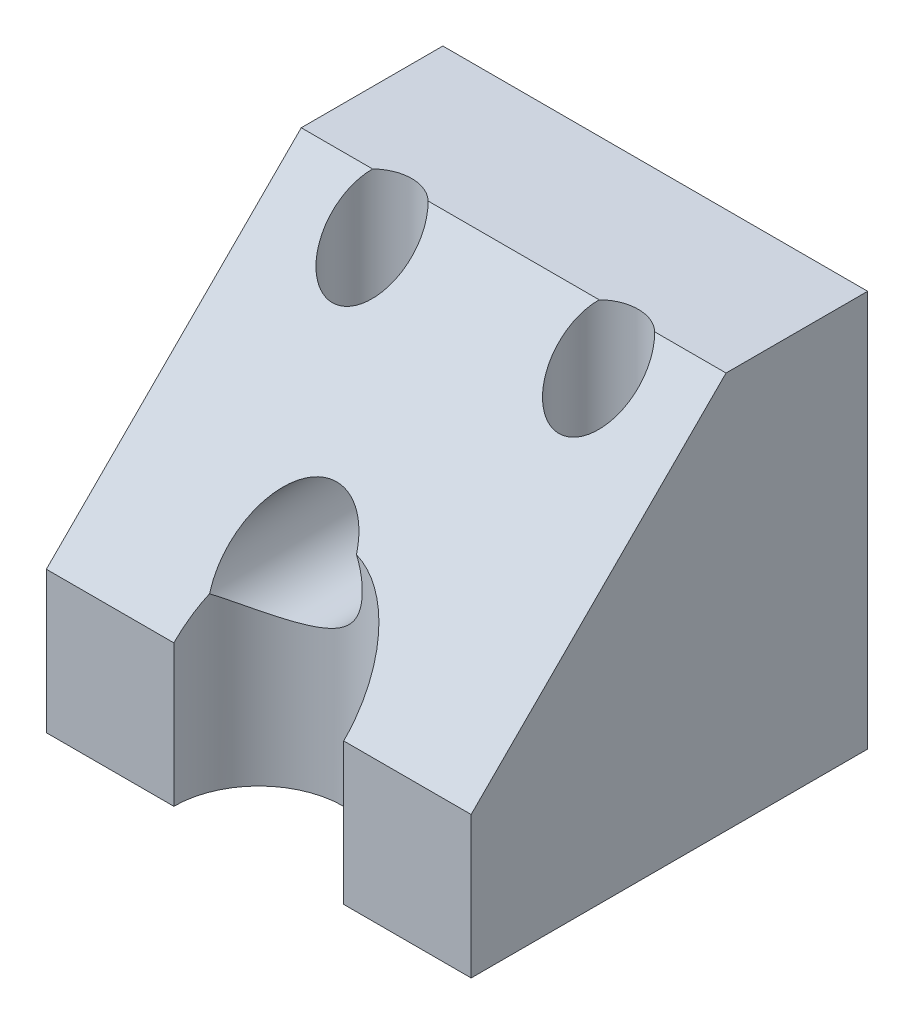
SolidWorks part; units mm, degrees
material "PLA"
ref_plane "前视基准面" through (0, 0, 0) normal (0, 0, 1) x (1, 0, 0)
ref_plane "上视基准面" through (0, 0, 0) normal (0, 1, 0) x (1, 0, 0)
ref_plane "右视基准面" through (0, 0, 0) normal (1, 0, 0) x (0, 0, -1)
sketch "草图1" plane through (0, 0, 0) normal (1, 0, 0) x (0, 0, -1)
  line L0 (-14, 0) -> (0, 0)
  line L1 (0, 0) -> (0, 14)
  line L2 (0, 14) -> (-5, 14)
  line L3 (-5, 14) -> (-14, 5)
  line L4 (-14, 5) -> (-14, 0)
  line L5 (0, 7) -> (-6, 7) construction
  line L6 (-6, 7) -> (-6, 0) construction
  dimension "D1" = 6
  dimension "D2" = 7
  dimension "D3" = 14
  dimension "D4" = 14
  dimension "D5" = 135
  dimension "D6" = 5
extrude "凸台-拉伸1" add sketch "草图1" along normal blind 15
sketch "草图2" plane through (0, 0, 0) normal (0, -1, 0) x (1, 0, 0)
  line L0 (3.5, 6) -> (11.5, 6) construction
  line L1 (15, 0) -> (0, 0) construction
  circle A0 centre (11.5, 6) radius 1.4
  circle A1 centre (3.5, 6) radius 1.4
  point P2 (7.5, 6)
  point P5 (7.5, 0)
  dimension "D3" = 2.8
  dimension "D1" = 6
  dimension "D2" = 8
extrude "切除-拉伸1" cut sketch "草图2" against normal through all and the other way through all
sketch "草图3" plane through (0, 0, 0) normal (0, 0, -1) x (-1, 0, 0)
  line L1 (-15, 0) -> (0, 0) construction
  line L2 (0, 0) -> (0, 14) construction
  circle A0 centre (-6.35, 7) radius 1.9
  dimension "D3" = 3.8
  dimension "D1" = 7
  dimension "D2" = 6.35
extrude "切除-拉伸2" cut sketch "草图3" against normal through all
sketch "草图4" plane through (0, 0, 0) normal (0, -1, 0) x (1, 0, 0)
  line L0 (15, 14) -> (0, 14) construction
  circle A0 centre (7.5, 14) radius 3
  dimension "D1" = 6
extrude "切除-拉伸3" cut sketch "草图4" against normal through all and the other way through all
